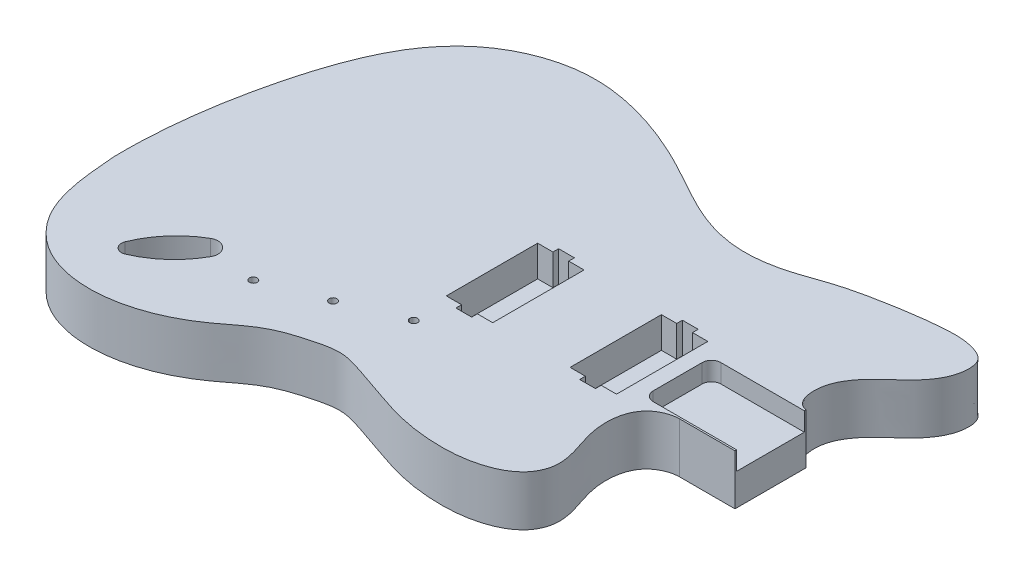
SolidWorks part; units mm, degrees
ref_plane "Front Plane" through (0, 0, 0) normal (0, 0, 1) x (1, 0, 0)
ref_plane "Top Plane" through (0, 0, 0) normal (0, 1, 0) x (1, 0, 0)
ref_plane "Right Plane" through (0, 0, 0) normal (1, 0, 0) x (0, 0, -1)
sketch "Sketch2" plane through (0, 0, 0) normal (0, 1, 0) x (1, 0, 0)
  line L0 (509.0855, 191.5535) -> (554.4949, 191.5535)
  line L1 (554.4949, 191.5535) -> (554.4949, 249.9042)
  spline S0 degree 3 poles (90.5, 145.7197) (89.802, 183.3719) (96.5115, 236.3559) (115.8703, 306.5164) (135.5707, 349.3246) (173.0336, 385.2407) (220.6034, 402.5174) (279.7221, 393.299) (325.5579, 372.5696) (360.6081, 351.7755) (386.6844, 340.6598) (415.7786, 334.7113) (447.1675, 339.5076) (478.0156, 351.7459) (511.6466, 358.9531) (545.9724, 364.2501) (573.4513, 365.2755) (591.2365, 357.3295) (592.8508, 344.0761) (589.2425, 328.8494) (577.7, 314.2188) (562.4516, 301.7992) (550.0875, 288.2032) (541.8827, 269.9894) (545.5906, 251.2138) (554.4949, 249.9042) knots 0 0 0 0 0.137751 0.193404 0.266847 0.306069 0.381118 0.441464 0.520689 0.563923 0.590496 0.624102 0.671189 0.704011 0.745452 0.796656 0.830646 0.84661 0.860786 0.874697 0.903947 0.926063 0.947253 0.969961 1 1 1 1
  spline S1 degree 3 poles (90.5, 145.7197) (92.4027, 123.4869) (94.5261, 85.4215) (130.6362, 48.442) (169.8541, 39.2771) (210.8802, 45.7294) (245.2276, 62.9929) (272.4925, 87.2085) (299.8359, 95.5929) (323.8744, 101.1643) (342.3349, 94.9892) (364.3051, 87.8012) (391.5059, 77.4496) (425.1945, 72.74) (458.2541, 75.0406) (483.5625, 86.4321) (492.2451, 105.918) (490.2352, 124.6442) (479.5746, 148.0582) (481.1185, 182.6154) (501.8325, 191.5097) (509.0855, 191.5535) knots 0 0 0 0 0.116243 0.176387 0.246646 0.309541 0.382136 0.436863 0.490014 0.524292 0.558002 0.585151 0.641136 0.703675 0.753688 0.808745 0.830257 0.856511 0.899936 0.963113 1 1 1 1
extrude "Boss-Extrude1" add sketch "Sketch2" along normal blind 41.275
sketch "Sketch6" plane through (0, 41.275, 0) normal (0, 1, 0) x (1, 0, 0)
  line L0 (554.4949, 191.5535) -> (554.4949, 249.9042) construction
  line L1 (478.2949, 248.5072) -> (554.4949, 248.5072)
  line L2 (478.2949, 248.5072) -> (478.2949, 192.9447)
  line L3 (478.2949, 192.9447) -> (554.4949, 192.9447)
  line L4 (554.4949, 248.5072) -> (554.4949, 192.9447)
  line L5 (478.2949, 248.5072) -> (554.4949, 192.9447) construction
  line L6 (478.2949, 192.9447) -> (554.4949, 248.5072) construction
  point P0 (516.3949, 220.726)
  dimension "D1" = 55.5625
  dimension "D2" = 1.397
  dimension "D3" = 76.2
extrude "Cut-Extrude4" cut sketch "Sketch6" against normal blind 15.24
fillet "Fillet5" radius 7.62 2 edges at (478.2949, 33.655, -192.9447) (478.2949, 33.655, -248.5072)
sketch "Sketch7" plane through (0, 41.275, 0) normal (0, 1, 0) x (1, 0, 0)
  line L0 (554.4949, 248.5072) -> (485.9149, 248.5072) construction
  line L1 (465.5949, 262.8582) -> (427.4949, 262.8582)
  line L2 (465.5949, 262.8582) -> (465.5949, 178.5302)
  line L3 (465.5949, 178.5302) -> (427.4949, 178.5302)
  line L4 (427.4949, 262.8582) -> (427.4949, 178.5302)
  line L6 (325.8949, 178.5302) -> (338.4304, 178.5302)
  line L7 (478.2949, 240.8872) -> (478.2949, 200.5647) construction
  line L8 (363.9949, 262.8582) -> (325.8949, 262.8582)
  line L9 (363.9949, 262.8582) -> (363.9949, 178.5302)
  line L10 (363.9949, 178.5302) -> (325.8949, 178.5302)
  line L11 (325.8949, 262.8582) -> (325.8949, 178.5302)
  line L12 (325.8949, 178.5302) -> (325.8949, 183.2038)
  line L13 (325.8949, 262.8582) -> (338.4304, 262.8582)
  line L14 (325.8949, 262.8582) -> (325.8949, 258.1846)
  line L15 (325.8949, 258.1846) -> (338.4304, 258.1846)
  line L16 (338.4304, 262.8582) -> (338.4304, 258.1846)
  line L17 (363.9949, 262.8582) -> (351.3844, 262.8582)
  line L18 (363.9949, 262.8582) -> (363.9949, 258.1846)
  line L19 (363.9949, 258.1846) -> (351.3844, 258.1846)
  line L20 (351.3844, 262.8582) -> (351.3844, 258.1846)
  line L21 (325.8949, 183.2038) -> (338.4304, 183.2038)
  line L22 (338.4304, 178.5302) -> (338.4304, 183.2038)
  line L23 (351.3844, 183.2038) -> (363.9949, 183.2038)
  line L24 (351.3844, 183.2038) -> (351.3844, 178.5302)
  line L25 (351.3844, 178.5302) -> (363.9949, 178.5302)
  line L26 (363.9949, 183.2038) -> (363.9949, 178.5302)
  line L27 (427.4949, 183.2038) -> (440.0479, 183.2038)
  line L28 (427.4949, 183.2038) -> (427.4949, 178.5302)
  line L29 (427.4949, 178.5302) -> (440.0479, 178.5302)
  line L30 (440.0479, 183.2038) -> (440.0479, 178.5302)
  line L31 (465.5949, 183.2038) -> (453.0019, 183.2038)
  line L32 (465.5949, 183.2038) -> (465.5949, 178.5302)
  line L33 (465.5949, 178.5302) -> (453.0019, 178.5302)
  line L34 (453.0019, 183.2038) -> (453.0019, 178.5302)
  line L35 (440.0479, 258.1846) -> (427.4949, 258.1846)
  line L36 (440.0479, 258.1846) -> (440.0479, 262.8582)
  line L37 (440.0479, 262.8582) -> (427.4949, 262.8582)
  line L38 (427.4949, 258.1846) -> (427.4949, 262.8582)
  line L39 (453.0019, 258.1846) -> (465.5949, 258.1846)
  line L40 (453.0019, 258.1846) -> (453.0019, 262.8582)
  line L41 (453.0019, 262.8582) -> (465.5949, 262.8582)
  line L42 (465.5949, 258.1846) -> (465.5949, 262.8582)
  dimension "D1" = 84.328
  dimension "D2" = 38.1
  dimension "D3" = 14.351
  dimension "D4" = 38.1
  dimension "D5" = 84.328
  dimension "D6" = 63.5
  dimension "D7" = 12.7
  dimension "D8" = 12.954
  dimension "D9" = 4.6736
  dimension "D10" = 4.6736
  dimension "D11" = 4.6736
  dimension "D12" = 12.954
  dimension "D13" = 12.954
extrude "Cut-Extrude6" cut sketch "Sketch7" against normal blind 25.4 contours L24 L23 L9 L19 L20 L8 L16 L15 L11 L21 L22 L10 | L39 L40 L1 L36 L35 L4 L27 L30 L3 L34 L31 L2
sketch "Sketch9" plane through (0, 41.275, 0) normal (0, 1, 0) x (1, 0, 0)
  line L0 (206.7368, 133.074) -> (149.6858, 75.0184) construction
  line L1 (193.0009, 119.0963) -> (196.2282, 145.3803) construction
  arc A0 (201.3437, 114.5002) -> (188.26, 127.3576) centre (193.0009, 119.0963) ccw
  arc A1 (155.5855, 89.9341) -> (164.4962, 81.1776) centre (161.8455, 87.3923) ccw
  arc A2 (164.4962, 81.1776) -> (201.3437, 114.5002) centre (134.6014, 151.2685) ccw
  arc A3 (188.26, 127.3576) -> (155.5855, 89.9341) centre (226.1875, 61.2672) ccw
  dimension "D2" = 76.2
  dimension "D3" = 76.2
  dimension "D1" = 37.5
extrude "Cut-Extrude7" cut sketch "Sketch9" against normal blind 25.4
sketch "Sketch10" plane through (0, 41.275, 0) normal (0, 1, 0) x (1, 0, 0)
  circle A0 centre (330.0191, 152.3256) radius 3.175
  circle A1 centre (282.9675, 133.1739) radius 3.175
  circle A2 centre (235.4455, 115.2212) radius 3.175
  dimension "D1" = 50.8
  dimension "D2" = 50.8
extrude "Cut-Extrude8" cut sketch "Sketch10" against normal blind 76.2
